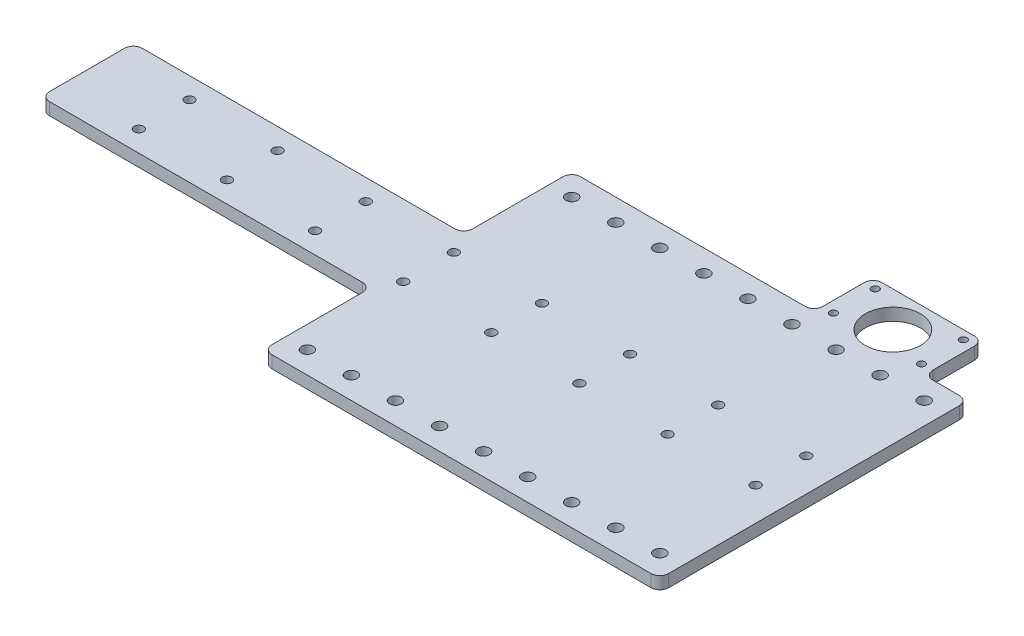
SolidWorks part; units mm, degrees
material "Acrylic (Medium-high impact)"
ref_plane "Front Plane" through (0, 0, 0) normal (0, 0, 1) x (1, 0, 0)
ref_plane "Top Plane" through (0, 0, 0) normal (0, 1, 0) x (1, 0, 0)
ref_plane "Right Plane" through (0, 0, 0) normal (1, 0, 0) x (0, 0, -1)
sketch "Sketch1" plane through (0, 0, 0) normal (0, 1, 0) x (1, 0, 0)
  line L0 (90, 140) -> (90, 50.8) construction
  line L1 (0, 0) -> (180, 0)
  line L2 (0, 0) -> (0, 140)
  line L3 (0, 140) -> (180, 140)
  line L4 (180, 0) -> (180, 140)
  line L9 (90, 50.8) -> (90, 0) construction
  line L10 (0, 70) -> (180, 70) construction
  dimension "D1" = 140
  dimension "D2" = 180
extrude "Boss-Extrude1" add sketch "Sketch1" along normal blind 5.588
sketch "Sketch3" plane through (0, 5.588, 0) normal (0, 1, 0) x (1, 0, 0)
  line L0 (90, 140) -> (90, 0) construction
  line L1 (0, 140) -> (180, 140) construction
  line L2 (0, 0) -> (180, 0) construction
  line L3 (90, 130) -> (110, 130) construction
  line L4 (90, 70) -> (180, 70) construction
  line L5 (180, 0) -> (180, 140) construction
  line L6 (170, 130) -> (170, 110) construction
  line L7 (90, 70) -> (180, 140) construction
  circle A0 centre (90, 130) radius 2.65
  circle A1 centre (110, 130) radius 2.65
  circle A2 centre (130, 130) radius 2.65
  circle A3 centre (170, 130) radius 2.65
  circle A6 centre (30, 130) radius 2.65
  circle A7 centre (150, 130) radius 2.65
  circle A10 centre (10, 130) radius 2.65
  circle A11 centre (50, 130) radius 2.65
  circle A12 centre (70, 130) radius 2.65
  circle A13 centre (70, 10) radius 2.65
  circle A14 centre (50, 10) radius 2.65
  circle A15 centre (10, 10) radius 2.65
  circle A18 centre (150, 10) radius 2.65
  circle A19 centre (30, 10) radius 2.65
  circle A22 centre (170, 10) radius 2.65
  circle A23 centre (130, 10) radius 2.65
  circle A24 centre (110, 10) radius 2.65
  circle A25 centre (90, 10) radius 2.65
  dimension "D1" = 5.3
  dimension "D2" = 10
  dimension "D4" = 20
  dimension "D3" = 5
extrude "Cut-Extrude2" cut sketch "Sketch3" against normal through all
sketch "Sketch4" plane through (0, 5.588, 0) normal (0, 1, 0) x (1, 0, 0)
  line L0 (135, 150.8) -> (135, 157.7623) construction
  line L1 (160, 140) -> (141.2936, 140)
  line L2 (160, 140) -> (160, 166.8)
  line L3 (160, 166.8) -> (110, 166.8)
  line L4 (110, 140) -> (110, 166.8)
  line L5 (180, 121.8) -> (95.9728, 121.8) construction
  line L6 (180, 0) -> (180, 140) construction
  line L7 (0, 140) -> (180, 140) construction
  line L8 (128.7064, 140) -> (110, 140)
  arc A0 (141.2936, 140) -> (128.7064, 140) centre (135, 150.8) ccw
  dimension "D2" = 25
  dimension "D5" = 29
  dimension "D1" = 18.2
  dimension "D3" = 50
  dimension "D4" = 16
  dimension "D6" = 20
extrude "Boss-Extrude2" add sketch "Sketch4" against normal through all
sketch "Sketch5" plane through (0, 5.588, 0) normal (0, 1, 0) x (1, 0, 0)
  circle A0 centre (135, 150.8) radius 12.5
  arc A1 (141.2936, 140) -> (128.7064, 140) centre (135, 150.8) ccw construction
extrude "Cut-Extrude3" cut sketch "Sketch5" against normal through all
sketch "Sketch6" plane through (0, 5.588, 0) normal (0, 1, 0) x (1, 0, 0)
  line L0 (115, 143.8) -> (115, 162.8) construction
  line L1 (115, 162.8) -> (155, 162.8) construction
  line L2 (155, 162.8) -> (155, 143.8) construction
  line L3 (135, 162.8) -> (135, 150.8) construction
  circle A1 centre (115, 162.8) radius 1.65
  circle A2 centre (155, 162.8) radius 1.65
  circle A3 centre (155, 143.8) radius 1.65
  circle A4 centre (115, 143.8) radius 1.65
  dimension "D1" = 3.3
  dimension "D2" = 40
  dimension "D3" = 12
  dimension "D4" = 19
extrude "Cut-Extrude4" cut sketch "Sketch6" against normal through all
sketch "Sketch7" plane through (0, 5.588, 0) normal (0, 1, 0) x (1, 0, 0)
  line L0 (180, 70) -> (-150, 70) construction
  line L1 (180, 0) -> (180, 140) construction
  line L2 (0, 0) -> (0, 140) construction
  line L3 (0, 49) -> (-150, 49)
  line L4 (0, 49) -> (0, 91)
  line L5 (0, 91) -> (-150, 91)
  line L6 (-150, 49) -> (-150, 91)
  dimension "D1" = 42
  dimension "D2" = 330
extrude "Boss-Extrude3" add sketch "Sketch7" against normal through all
sketch "Sketch2" plane through (0, 5.588, 0) normal (0, 1, 0) x (1, 0, 0)
  line L0 (0, 70) -> (180, 70) construction
  line L2 (180, 0) -> (180, 140) construction
  line L5 (165, 81.5) -> (165, 70) construction
  circle A0 centre (125, 81.5) radius 2.15
  circle A1 centre (125, 58.5) radius 2.15
  circle A2 centre (85, 81.5) radius 2.15
  circle A3 centre (165, 81.5) radius 2.15
  circle A4 centre (85, 58.5) radius 2.15
  circle A5 centre (165, 58.5) radius 2.15
  circle A6 centre (45, 81.5) radius 2.15
  circle A7 centre (45, 58.5) radius 2.15
  circle A8 centre (5, 81.5) radius 2.15
  circle A9 centre (5, 58.5) radius 2.15
  circle A10 centre (-35, 81.5) radius 2.15
  circle A11 centre (-35, 58.5) radius 2.15
  circle A12 centre (-75, 81.5) radius 2.15
  circle A13 centre (-75, 58.5) radius 2.15
  circle A14 centre (-115, 81.5) radius 2.15
  circle A15 centre (-115, 58.5) radius 2.15
  circle A16 centre (-155, 81.5) radius 2.15
  circle A17 centre (-155, 58.5) radius 2.15
  dimension "D1" = 11.5
  dimension "D2" = 9
  dimension "D3" = 40
  dimension "D4" = 4.3
  dimension "D5" = 15
extrude "Cut-Extrude1" cut sketch "Sketch2" against normal through all
fillet "Fillet1" radius 4 12 edges at (0, 2.794, -140) (0, 2.794, 0) (180, 2.794, 0) (180, 2.794, -140) (160, 2.794, -140) (160, 2.794, -166.8) (110, 2.794, -166.8) (110, 2.794, -140) (-150, 2.794, -49) (-150, 2.794, -91)
